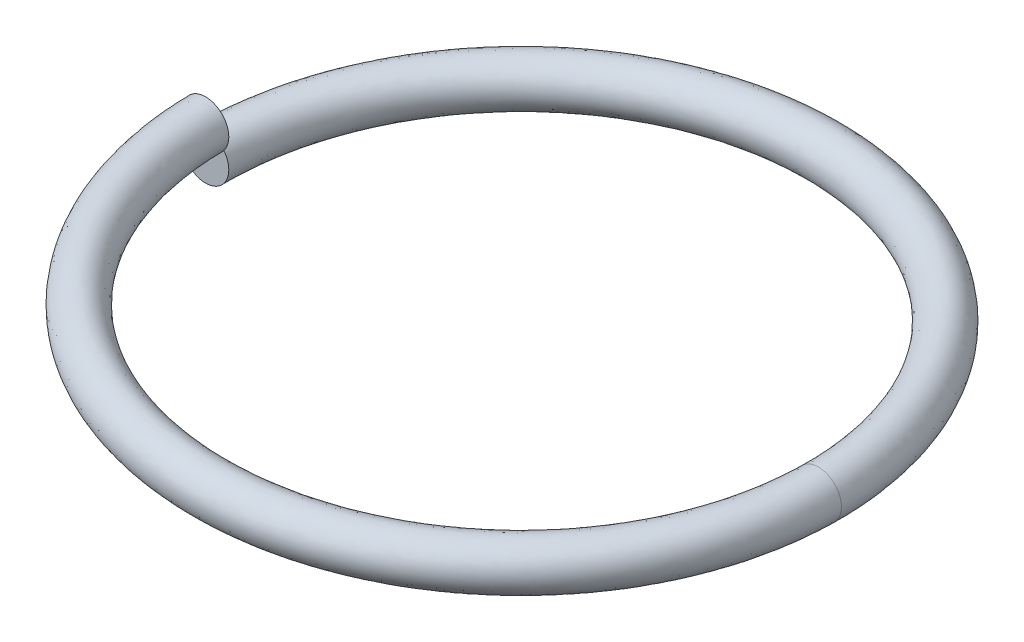
SolidWorks part; units mm, degrees
ref_plane "Alzado" through (0, 0, 0) normal (0, 0, 1) x (1, 0, 0)
ref_plane "Planta" through (0, 0, 0) normal (0, 1, 0) x (1, 0, 0)
ref_plane "Vista lateral" through (0, 0, 0) normal (1, 0, 0) x (0, 0, -1)
sketch "Croquis1" plane through (0, 0, 0) normal (0, 1, 0) x (1, 0, 0)
  circle A0 centre (0, 0) radius 8.6
  dimension "D1" = 17.2
curve "Hélice/Espiral1" pitch 0.8 height 0.8 turns 1
sketch "Croquis2" plane through (0, 0, 0) normal (0, 0, 1) x (1, 0, 0)
  circle A0 centre (-8.6, 0) radius 0.65
sweep "Barrer1" add profiles "Croquis2" path "Hélice/Espiral1"
sketch "Croquis3" plane through (0, 0, 0) normal (0, 1, 0) x (1, 0, 0)
  circle A0 centre (0, 0) radius 5.1262
